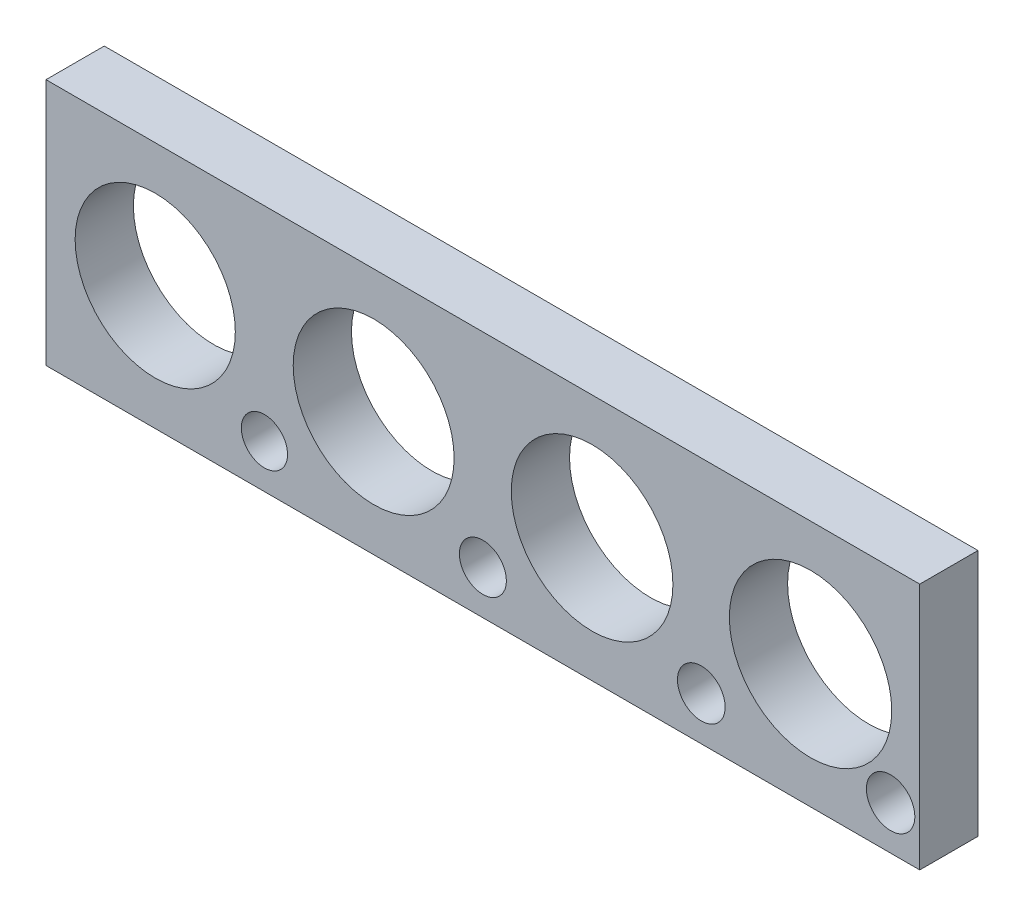
SolidWorks part; units mm, degrees
ref_plane "Front Plane" through (0, 0, 0) normal (0, 0, 1) x (1, 0, 0)
ref_plane "Top Plane" through (0, 0, 0) normal (0, 1, 0) x (1, 0, 0)
ref_plane "Right Plane" through (0, 0, 0) normal (1, 0, 0) x (0, 0, -1)
sketch "Coupon_plate_profile" plane through (0, 0, 0) normal (0, 0, 1) x (1, 0, 0)
  line L1 (-60, -17) -> (60, -17)
  line L2 (-60, -17) -> (-60, 17)
  line L3 (-60, 17) -> (60, 17)
  line L4 (60, -17) -> (60, 17)
  dimension "D1" = 120
  dimension "D2" = 34
  dimension "D3" = 60
  dimension "D4" = 17
extrude "Coupon_plate" add sketch "Coupon_plate_profile" along normal blind 8
sketch "Bearing_seat_trial_22p0_22p1_22p2_22p3" plane through (0, 0, 0) normal (0, 0, 1) x (1, 0, 0)
  circle A0 centre (-45, 0) radius 11
  circle A1 centre (-15, 0) radius 11.05
  circle A2 centre (15, 0) radius 11.1
  circle A3 centre (45, 0) radius 11.15
  dimension "D1" = 22
  dimension "D2" = 22.1
  dimension "D3" = 22.2
  dimension "D4" = 22.3
  dimension "D5" = 15
  dimension "D6" = 45
  dimension "D7" = 15
  dimension "D8" = 45
extrude "Bearing_fit_trial_through" cut sketch "Bearing_seat_trial_22p0_22p1_22p2_22p3" along normal through all from offset 1
sketch "Dowel_trial_6p35_6p45_6p55_6p65" plane through (0, 0, 0) normal (0, 0, 1) x (1, 0, 0)
  circle A0 centre (-30, -11) radius 3.175
  circle A1 centre (0, -11) radius 3.225
  circle A2 centre (30, -11) radius 3.275
  circle A3 centre (56, -11) radius 3.325
  dimension "D1" = 6.35
  dimension "D2" = 6.45
  dimension "D3" = 6.55
  dimension "D4" = 6.65
  dimension "D5" = 30
  dimension "D6" = 56
  dimension "D7" = 30
  dimension "D8" = 11
extrude "Dowel_fit_trial_through" cut sketch "Dowel_trial_6p35_6p45_6p55_6p65" along normal through all from offset 1
